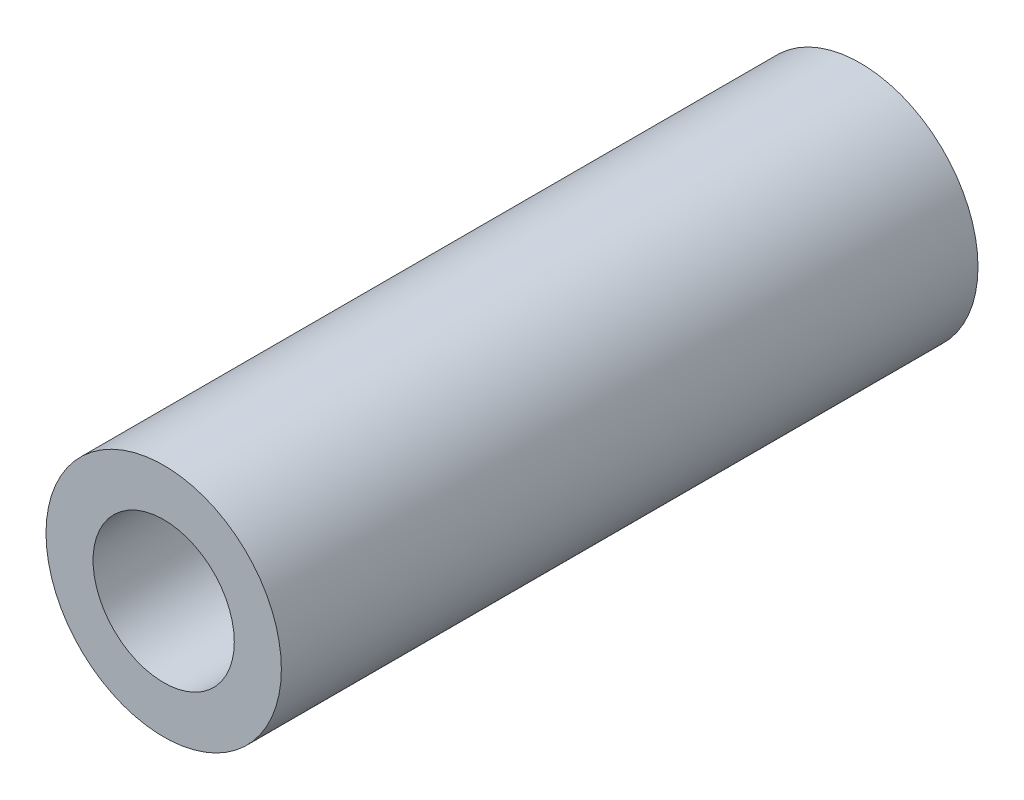
SolidWorks part; units mm, degrees
material "5052-H34"
ref_plane "正面" through (0, 0, 0) normal (0, 0, 1) x (1, 0, 0)
ref_plane "平面" through (0, 0, 0) normal (0, 1, 0) x (1, 0, 0)
ref_plane "右側面" through (0, 0, 0) normal (1, 0, 0) x (0, 0, -1)
sketch "ｽｹｯﾁ1" plane through (0, 0, 0) normal (0, 0, 1) x (1, 0, 0)
  circle A0 centre (0, 0) radius 5
  circle A1 centre (0, 0) radius 3
  dimension "D1" = 6
  dimension "D2" = 10
extrude "ﾎﾞｽ - 押し出し1" add sketch "ｽｹｯﾁ1" along normal blind 29.6
